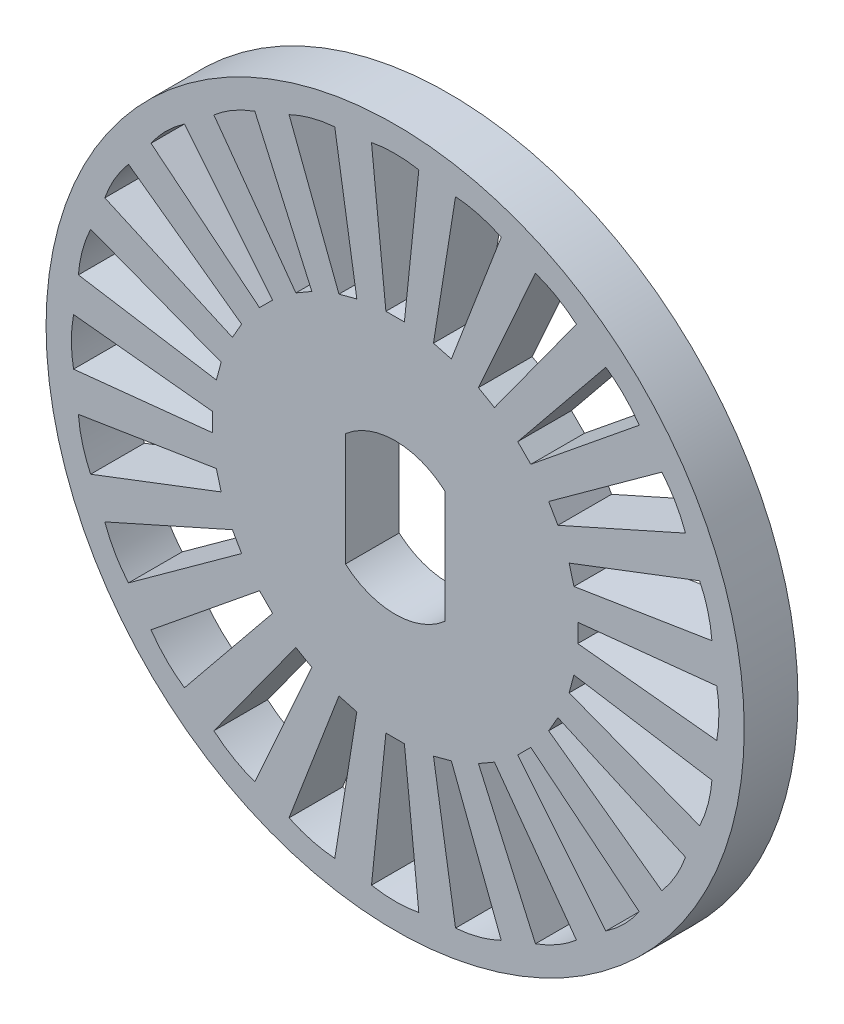
SolidWorks part; units mm, degrees
ref_plane "Front Plane" through (0, 0, 0) normal (0, 0, 1) x (1, 0, 0)
ref_plane "Top Plane" through (0, 0, 0) normal (0, 1, 0) x (1, 0, 0)
ref_plane "Right Plane" through (0, 0, 0) normal (1, 0, 0) x (0, 0, -1)
sketch "Sketch1" plane through (0, 0, 0) normal (0, 0, 1) x (1, 0, 0)
  line L0 (0, 29.3396) -> (0, -28.4316) construction
  line L1 (-34.5346, 0) -> (35.2675, 0) construction
  circle A0 centre (0, 0) radius 13
  dimension "D1" = 26
extrude "Boss-Extrude1" add sketch "Sketch1" along normal blind 2
sketch "Sketch2" plane through (0, 0, 2) normal (0, 0, 1) x (1, 0, 0)
  line L0 (0, 12.0457) -> (0, -12.3213) construction
  line L1 (-16.0712, 0) -> (16.7447, 0) construction
  line L2 (1.85, 2.1018) -> (1.85, -2.1018)
  line L3 (-1.85, 2.1018) -> (-1.85, -2.1018)
  arc A0 (-1.85, -2.1018) -> (1.85, -2.1018) centre (0, 0) ccw
  arc A1 (1.85, 2.1018) -> (-1.85, 2.1018) centre (0, 0) ccw
  point P11 (0, 0)
  dimension "D1" = 3.7
  dimension "D2" = 5.6
extrude "Cut-Extrude1" cut sketch "Sketch2" against normal blind 2
sketch "Sketch3" plane through (0, 0, 2) normal (0, 0, 1) x (1, 0, 0)
  line L0 (0, 13.934) -> (0, -12.3825) construction
  line L1 (-14.8773, 0) -> (14.2345, 0) construction
  line L2 (-0.3444, 6.8) -> (0.3444, 6.8)
  line L3 (0.3444, 6.8) -> (0.8813, 11.9756)
  line L4 (-0.3444, 6.8) -> (-0.8813, 11.9756)
  line L6 (2.0926, 6.4792) -> (3.9508, 11.3394)
  line L7 (1.4273, 6.6574) -> (2.0926, 6.4792)
  line L8 (1.4273, 6.6574) -> (2.2482, 11.7956)
  line L9 (3.6982, 5.7168) -> (6.751, 9.9305)
  line L10 (3.1018, 6.0612) -> (3.6982, 5.7168)
  line L11 (3.1018, 6.0612) -> (5.2245, 10.8118)
  line L12 (5.0518, 4.5648) -> (9.0912, 7.8448)
  line L13 (4.5648, 5.0518) -> (5.0518, 4.5648)
  line L14 (4.5648, 5.0518) -> (7.8448, 9.0912)
  line L15 (6.0612, 3.1018) -> (10.8118, 5.2245)
  line L16 (5.7168, 3.6982) -> (6.0612, 3.1018)
  line L17 (5.7168, 3.6982) -> (9.9305, 6.751)
  line L18 (6.6574, 1.4273) -> (11.7956, 2.2482)
  line L19 (6.4792, 2.0926) -> (6.6574, 1.4273)
  line L20 (6.4792, 2.0926) -> (11.3394, 3.9508)
  line L21 (6.8, -0.3444) -> (11.9756, -0.8813)
  line L22 (6.8, 0.3444) -> (6.8, -0.3444)
  line L23 (6.8, 0.3444) -> (11.9756, 0.8813)
  line L24 (6.4792, -2.0926) -> (11.3394, -3.9508)
  line L25 (6.6574, -1.4273) -> (6.4792, -2.0926)
  line L26 (6.6574, -1.4273) -> (11.7956, -2.2482)
  line L27 (5.7168, -3.6982) -> (9.9305, -6.751)
  line L28 (6.0612, -3.1018) -> (5.7168, -3.6982)
  line L29 (6.0612, -3.1018) -> (10.8118, -5.2245)
  line L30 (4.5648, -5.0518) -> (7.8448, -9.0912)
  line L31 (5.0518, -4.5648) -> (4.5648, -5.0518)
  line L32 (5.0518, -4.5648) -> (9.0912, -7.8448)
  line L33 (3.1018, -6.0612) -> (5.2245, -10.8118)
  line L34 (3.6982, -5.7168) -> (3.1018, -6.0612)
  line L35 (3.6982, -5.7168) -> (6.751, -9.9305)
  line L36 (1.4273, -6.6574) -> (2.2482, -11.7956)
  line L37 (2.0926, -6.4792) -> (1.4273, -6.6574)
  line L38 (2.0926, -6.4792) -> (3.9508, -11.3394)
  line L39 (-0.3444, -6.8) -> (-0.8813, -11.9756)
  line L40 (0.3444, -6.8) -> (-0.3444, -6.8)
  line L41 (0.3444, -6.8) -> (0.8813, -11.9756)
  line L42 (-2.0926, -6.4792) -> (-3.9508, -11.3394)
  line L43 (-1.4273, -6.6574) -> (-2.0926, -6.4792)
  line L44 (-1.4273, -6.6574) -> (-2.2482, -11.7956)
  line L45 (-3.6982, -5.7168) -> (-6.751, -9.9305)
  line L46 (-3.1018, -6.0612) -> (-3.6982, -5.7168)
  line L47 (-3.1018, -6.0612) -> (-5.2245, -10.8118)
  line L48 (-5.0518, -4.5648) -> (-9.0912, -7.8448)
  line L49 (-4.5648, -5.0518) -> (-5.0518, -4.5648)
  line L50 (-4.5648, -5.0518) -> (-7.8448, -9.0912)
  line L51 (-6.0612, -3.1018) -> (-10.8118, -5.2245)
  line L52 (-5.7168, -3.6982) -> (-6.0612, -3.1018)
  line L53 (-5.7168, -3.6982) -> (-9.9305, -6.751)
  line L54 (-6.6574, -1.4273) -> (-11.7956, -2.2482)
  line L55 (-6.4792, -2.0926) -> (-6.6574, -1.4273)
  line L56 (-6.4792, -2.0926) -> (-11.3394, -3.9508)
  line L57 (-6.8, 0.3444) -> (-11.9756, 0.8813)
  line L58 (-6.8, -0.3444) -> (-6.8, 0.3444)
  line L59 (-6.8, -0.3444) -> (-11.9756, -0.8813)
  line L60 (-6.4792, 2.0926) -> (-11.3394, 3.9508)
  line L61 (-6.6574, 1.4273) -> (-6.4792, 2.0926)
  line L62 (-6.6574, 1.4273) -> (-11.7956, 2.2482)
  line L63 (-5.7168, 3.6982) -> (-9.9305, 6.751)
  line L64 (-6.0612, 3.1018) -> (-5.7168, 3.6982)
  line L65 (-6.0612, 3.1018) -> (-10.8118, 5.2245)
  line L66 (-4.5648, 5.0518) -> (-7.8448, 9.0912)
  line L67 (-5.0518, 4.5648) -> (-4.5648, 5.0518)
  line L68 (-5.0518, 4.5648) -> (-9.0912, 7.8448)
  line L69 (-3.1018, 6.0612) -> (-5.2245, 10.8118)
  line L70 (-3.6982, 5.7168) -> (-3.1018, 6.0612)
  line L71 (-3.6982, 5.7168) -> (-6.751, 9.9305)
  line L72 (-1.4273, 6.6574) -> (-2.2482, 11.7956)
  line L73 (-2.0926, 6.4792) -> (-1.4273, 6.6574)
  line L74 (-2.0926, 6.4792) -> (-3.9508, 11.3394)
  arc A2 (1.85, 2.1018) -> (-1.85, 2.1018) centre (0, 0) ccw construction
  spline S0 degree 2 poles (-0.8813, 11.9756) (0, 12.1388) (0.8813, 11.9756) knots 0 0 0 1 1 1
  spline S1 degree 2 poles (2.2482, 11.7956) (3.1417, 11.7252) (3.9508, 11.3394) knots 0 0 0 1 1 1
  spline S2 degree 2 poles (5.2245, 10.8118) (6.0694, 10.5125) (6.751, 9.9305) knots 0 0 0 1 1 1
  spline S3 degree 2 poles (7.8448, 9.0912) (8.5834, 8.5834) (9.0912, 7.8448) knots 0 0 0 1 1 1
  spline S4 degree 2 poles (9.9305, 6.751) (10.5125, 6.0694) (10.8118, 5.2245) knots 0 0 0 1 1 1
  spline S5 degree 2 poles (11.3394, 3.9508) (11.7252, 3.1417) (11.7956, 2.2482) knots 0 0 0 1 1 1
  spline S6 degree 2 poles (11.9756, 0.8813) (12.1388, 0) (11.9756, -0.8813) knots 0 0 0 1 1 1
  spline S7 degree 2 poles (11.7956, -2.2482) (11.7252, -3.1417) (11.3394, -3.9508) knots 0 0 0 1 1 1
  spline S8 degree 2 poles (10.8118, -5.2245) (10.5125, -6.0694) (9.9305, -6.751) knots 0 0 0 1 1 1
  spline S9 degree 2 poles (9.0912, -7.8448) (8.5834, -8.5834) (7.8448, -9.0912) knots 0 0 0 1 1 1
  spline S10 degree 2 poles (6.751, -9.9305) (6.0694, -10.5125) (5.2245, -10.8118) knots 0 0 0 1 1 1
  spline S11 degree 2 poles (3.9508, -11.3394) (3.1417, -11.7252) (2.2482, -11.7956) knots 0 0 0 1 1 1
  spline S12 degree 2 poles (0.8813, -11.9756) (0, -12.1388) (-0.8813, -11.9756) knots 0 0 0 1 1 1
  spline S13 degree 2 poles (-2.2482, -11.7956) (-3.1417, -11.7252) (-3.9508, -11.3394) knots 0 0 0 1 1 1
  spline S14 degree 2 poles (-5.2245, -10.8118) (-6.0694, -10.5125) (-6.751, -9.9305) knots 0 0 0 1 1 1
  spline S15 degree 2 poles (-7.8448, -9.0912) (-8.5834, -8.5834) (-9.0912, -7.8448) knots 0 0 0 1 1 1
  spline S16 degree 2 poles (-9.9305, -6.751) (-10.5125, -6.0694) (-10.8118, -5.2245) knots 0 0 0 1 1 1
  spline S17 degree 2 poles (-11.3394, -3.9508) (-11.7252, -3.1417) (-11.7956, -2.2482) knots 0 0 0 1 1 1
  spline S18 degree 2 poles (-11.9756, -0.8813) (-12.1388, 0) (-11.9756, 0.8813) knots 0 0 0 1 1 1
  spline S19 degree 2 poles (-11.7956, 2.2482) (-11.7252, 3.1417) (-11.3394, 3.9508) knots 0 0 0 1 1 1
  spline S20 degree 2 poles (-10.8118, 5.2245) (-10.5125, 6.0694) (-9.9305, 6.751) knots 0 0 0 1 1 1
  spline S21 degree 2 poles (-9.0912, 7.8448) (-8.5834, 8.5834) (-7.8448, 9.0912) knots 0 0 0 1 1 1
  spline S22 degree 2 poles (-6.751, 9.9305) (-6.0694, 10.5125) (-5.2245, 10.8118) knots 0 0 0 1 1 1
  spline S23 degree 2 poles (-3.9508, 11.3394) (-3.1417, 11.7252) (-2.2482, 11.7956) knots 0 0 0 1 1 1
  point P91 (0, 0)
  point P121 (0, 0)
  point P122 (0, 0)
  point P137 (0, 0)
  point P180 (0, 0)
  point P181 (0, 0)
  dimension "D2" = 4
  dimension "D1" = 24
extrude "Cut-Extrude2" cut sketch "Sketch3" against normal blind 2
